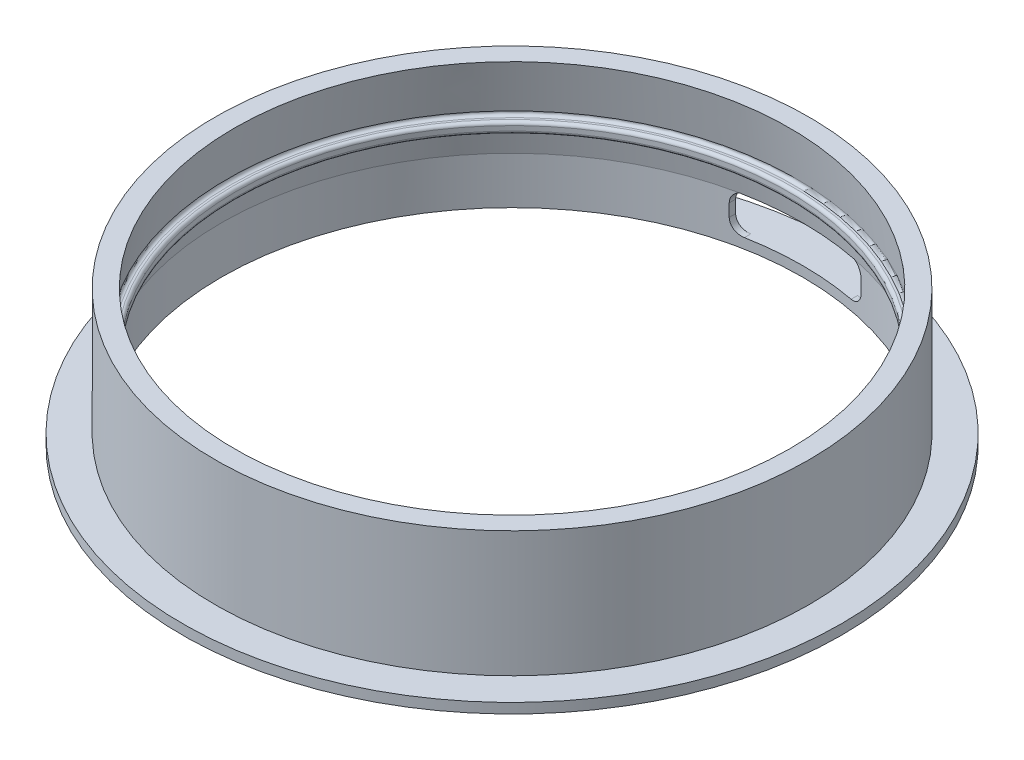
SolidWorks part; units mm, degrees
ref_plane "Front Plane" through (0, 0, 0) normal (0, 0, 1) x (1, 0, 0)
ref_plane "Top Plane" through (0, 0, 0) normal (0, 1, 0) x (1, 0, 0)
ref_plane "Right Plane" through (0, 0, 0) normal (1, 0, 0) x (0, 0, -1)
sketch "Sketch2" plane through (0, 0, 0) normal (0, 0, 1) x (1, 0, 0)
  line L0 (46.3, 0) -> (46.3, 21.6)
  line L1 (46.3, 21.6) -> (47.3, 21.6)
  line L2 (47.3, 21.6) -> (47.3, 1.6)
  line L3 (47.3, 1.6) -> (52.5, 1.6)
  line L4 (52.5, 1.6) -> (52.5, 0)
  line L5 (52.5, 0) -> (46.3, 0)
  line L6 (0, -1000) -> (0, 49000) construction
  dimension "D1" = 52.5
  dimension "D2" = 46.3
  dimension "D3" = 20
  dimension "D4" = 1.6
  dimension "D5" = 1
revolve "Revolve1" add sketch "Sketch2" angle 360 about L6
sketch "Sketch4" plane through (0, 0, 0) normal (0, 0, 1) x (1, 0, 0)
  line L1 (-10.5, 7.6) -> (10.5, 7.6)
  line L2 (-10.5, 7.6) -> (-10.5, 1.6)
  line L3 (-10.5, 1.6) -> (10.5, 1.6)
  line L4 (10.5, 7.6) -> (10.5, 1.6)
  line L5 (-10.5, 7.6) -> (10.5, 1.6) construction
  line L6 (-10.5, 1.6) -> (10.5, 7.6) construction
  line L7 (52.5, 1.6) -> (-52.5, 1.6) construction
  point P0 (0, 4.6)
  dimension "D1" = 21
  dimension "D2" = 6
extrude "Cut-Extrude1" cut sketch "Sketch4" against normal up to next
fillet "Fillet1" radius 2 4 edges at (10.5, 1.6, -45.6068) (10.5, 7.6, -45.6068) (-10.5, 7.6, -45.6068) (-10.5, 1.6, -45.6068)
sketch "Sketch5" plane through (0, 0, 0) normal (0, 0, 1) x (1, 0, 0)
  line L0 (52.5, 1.6) -> (-52.5, 1.6) construction
  circle A0 centre (0, 4.85) radius 2.25
  dimension "D1" = 4.5
  dimension "D2" = 3.25
sketch "Sketch6" plane through (0, 0, 0) normal (0, 0, 1) x (1, 0, 0)
  line L0 (-46.3, 21.6) -> (-46.3, 7.5)
  line L1 (-46.3, 7.5) -> (-44.243, 21.6)
  line L2 (-44.243, 21.6) -> (-46.3, 21.6)
  line L3 (-46.3, 0) -> (46.3, 0) construction
  line L4 (-45.6873, 11.7) -> (-44, 11.7)
  line L5 (-44, 11.7) -> (-44, 13.45)
  line L6 (-44, 13.45) -> (-45.432, 13.45)
  line L7 (0, -1000) -> (0, 49000) construction
  dimension "D1" = 7.5
  dimension "D2" = 8.3
  dimension "D3" = 4.2
  dimension "D4" = 1.75
  dimension "D5" = 44
revolve "Revolve2" add sketch "Sketch6" angle 360 about L7
fillet "Fillet2" radius 0.5 4 edges at (45.6873, 11.7, 0) (44, 11.7, 0) (45.432, 13.45, 0) (44, 13.45, 0)
